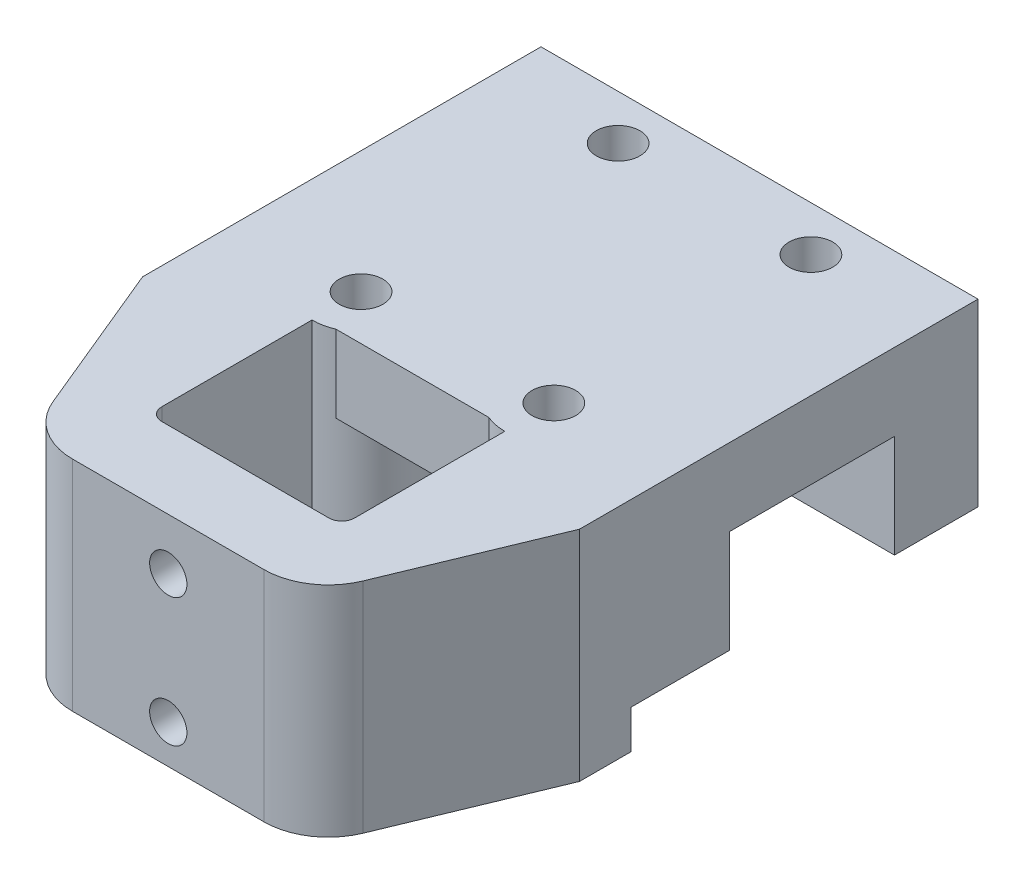
SolidWorks part; units mm, degrees
ref_plane "Front" through (0, 0, 0) normal (0, 0, 1) x (1, 0, 0)
ref_plane "Top" through (0, 0, 0) normal (0, 1, 0) x (1, 0, 0)
ref_plane "Right" through (0, 0, 0) normal (1, 0, 0) x (0, 0, -1)
sketch "Sketch1" plane through (0, 0, 0) normal (0, 1, 0) x (1, 0, 0)
  line B0 (17, 0) -> (0, 0) construction
  line B1 (17, -12) -> (11, -12)
  line B2 (17, -12) -> (17, 12)
  line B3 (17, 12) -> (11, 12)
  line B4 (-17, -12) -> (-17, 12)
  line B5 (-11, 12) -> (-11, 13.5)
  line B6 (11, -13.5) -> (-11, -13.5)
  line B7 (11, -13.5) -> (11, -12)
  line B8 (11, 13.5) -> (-11, 13.5)
  line B9 (-11, -13.5) -> (-11, -12)
  line B10 (-11, 12) -> (-17, 12)
  line B11 (-11, -12) -> (-17, -12)
  line B12 (0, 13.5) -> (0, 0) construction
  line B13 (7.5, -10) -> (-7.5, -10) construction
  line B14 (7.5, -10) -> (7.5, 10) construction
  line B15 (7.5, 10) -> (-7.5, 10) construction
  line B16 (-7.5, -10) -> (-7.5, 10) construction
  line B17 (7.5, -10) -> (-7.5, 10) construction
  line B18 (7.5, 10) -> (-7.5, -10) construction
sketch_block_instance "TW-04-12-1"
sketch_block "TW-04-12" parameters "D1"=22, "D2"=34, "D3"=27, "D4"=24, "D5"=20, "D6"=15
sketch "Sketch2" plane through (0, 0, 0) normal (0, 1, 0) x (1, 0, 0)
  line L0 (7.5, -9.8166) -> (-7.5, -9.8166) construction
  line L1 (7.5, -10) -> (7.5, 10) construction
  line L2 (7.5, -5.8166) -> (186, -5.8166) construction
  line L4 (-186, -5.8166) -> (-7.5, -5.8166)
  line L5 (-3.7504, -11.2097) -> (-5.4525, -15.7909)
  line L6 (5.4525, -15.7909) -> (3.7504, -11.2097)
  line L7 (7.5, -5.8166) -> (186, -5.8166)
  line L8 (186, 5.8166) -> (-186, 5.8166)
  line L11 (0, -17.8166) -> (0, 0) construction
  line L13 (-186, 0) -> (186, 0) construction
  arc A0 (-186, 5.8166) -> (-186, -5.8166) centre (-186, 0) ccw
  arc A1 (-7.5, -5.8166) -> (-3.7504, -11.2097) centre (-7.5, -9.8166) cw
  arc A2 (-5.4525, -15.7909) -> (5.4525, -15.7909) centre (0, -17.8166) ccw
  arc A4 (3.7504, -11.2097) -> (7.5, -5.8166) centre (7.5, -9.8166) cw
  arc A5 (186, -5.8166) -> (186, 5.8166) centre (186, 0) ccw
  circle B0 centre (186, 0) radius 5.8166
  circle B1 centre (-186, 0) radius 5.8166
  circle B2 centre (0, -17.8166) radius 5.8166
  circle B3 centre (7.5, -9.8166) radius 4
  circle B4 centre (-7.5, -9.8166) radius 4
  dimension "D1" = 8
  dimension "D7" = 372
sketch_block_instance "MXL-Pulley1163mmpd-1"
sketch_block "MXL-Pulley1163mmpd" parameters "D1"=11.6332
sketch_block_instance "MXL-Pulley1163mmpd-2"
sketch_block_instance "MXL-Pulley1163mmpd-4"
sketch_block_instance "Belt Guide Curve-1"
sketch_block "Belt Guide Curve" parameters "D1"=4.7507
sketch_block_instance "Belt Guide Curve-2"
other "Belt1"
sketch "Sketch3" plane through (0, 0, 0) normal (0, 1, 0) x (1, 0, 0)
  line L0 (11, 13.5) -> (-11, 13.5) construction
  line L1 (17, 13.5) -> (-17, 13.5)
  line L2 (17, 13.5) -> (17, -32.5)
  line L3 (17, -32.5) -> (-17, -32.5)
  line L4 (-17, 13.5) -> (-17, -32.5)
  line L5 (17, -12) -> (17, 12) construction
  line L6 (-17, -12) -> (-17, 12) construction
  dimension "D1" = 46
extrude "Boss-Extrude1" add sketch "Sketch3" against normal blind 14
hole_wizard "M3 Clearance Hole1" positions "Sketch5" profile "Sketch4" hole size "M3" standard "Ansi Metric" end condition through all
sketch "Sketch5" plane through (0, 0, 0) normal (0, 1, 0) x (-1, 0, 0)
  point P0 (7.5, 10)
  point P1 (7.5, -10)
  point P4 (-7.5, -10)
  point P7 (-7.5, 10)
sketch "Sketch4" plane through (-7.5, 0, 10) normal (1, 0, 0) x (0, 0, 1)
  line L0 (0, 0) -> (0, 14)
  line L1 (0, 14) -> (1.7, 14)
  line L2 (1.7, 14) -> (1.7, 0)
  line L5 (1.7, 0) -> (0, 0)
  line L11 (0, -6.35) -> (0, 107.95) construction
  dimension "Thru Hole Dia." = 3.4
  dimension "Thru Hole Depth" = 14
sketch "Sketch6" plane through (0, 0, 0) normal (1, 0, 0) x (0, 0, -1)
  line L0 (-32.5, -14) -> (13.5, -14) construction
  line L1 (-5.8166, -14) -> (7, -14)
  line L2 (-5.8166, -14) -> (-5.8166, -6)
  line L3 (-5.8166, -6) -> (7, -6)
  line L4 (7, -14) -> (7, -6)
  line L5 (13.5, -14) -> (13.5, 0) construction
  point P8 (-5.8166, 0)
  dimension "D1" = 6.5
  dimension "D2" = 8
  dimension "D3" = 12.8166
extrude "Cut-Extrude1" cut sketch "Sketch6" against normal through all and the other way through all
sketch "Sketch7" plane through (0, -6, 0) normal (0, 1, 0) x (1, 0, 0)
  line L1 (-7.5, -26.5) -> (7.5, -26.5)
  line L3 (0, -17.8166) -> (0, 0) construction
  line L4 (0, -17.8166) -> (0, 0) construction
  line L5 (-17, -32.5) -> (17, -32.5) construction
  line L6 (-17, -5.8166) -> (17, -5.8166) construction
  line L7 (-7.5, -5.8166) -> (7.5, -5.8166)
  line L8 (-7.5, -13.8166) -> (-7.5, -26.5)
  line L9 (7.5, -13.8166) -> (7.5, -26.5)
  arc A0 (-7.5, -13.8166) -> (-7.5, -5.8166) centre (-7.5, -9.8166) ccw
  arc A1 (7.5, -5.8166) -> (7.5, -13.8166) centre (7.5, -9.8166) ccw
  circle A2 centre (7.5, -9.8166) radius 4 construction
  circle A3 centre (-7.5, -9.8166) radius 4 construction
  dimension "D2" = 15
  dimension "D1" = 6
extrude "Cut-Extrude2" cut sketch "Sketch7" against normal through all
sketch "Sketch12" plane through (0, -6, 0) normal (0, -1, 0) x (1, 0, 0)
  line L1 (11, 13.5) -> (-11, 13.5) construction
  line L3 (5.9403, 13.5) -> (-5.9403, 13.5)
  line L16 (7.5, 26.5) -> (-7.5, 26.5)
  line L17 (-7.5, 26.5) -> (-7.5, 13.8166)
  line L19 (-7.5, 5.8166) -> (-17, 5.8166)
  line L20 (-17, 5.8166) -> (-17, -7)
  line L21 (-17, -7) -> (17, -7)
  line L22 (17, -7) -> (17, 5.8166)
  line L23 (17, 5.8166) -> (7.5, 5.8166)
  line L25 (7.5, 13.8166) -> (7.5, 26.5)
  line L29 (7.5, 26.5) -> (-7.5, 26.5)
  line L30 (-7.5, 26.5) -> (-7.5, 13.8166)
  line L38 (7.5, 13.8166) -> (7.5, 26.5)
  arc A8 (-7.5, 5.8166) -> (-7.5, 13.8166) centre (-7.5, 9.8166) ccw
  arc A9 (7.5, 13.8166) -> (7.5, 5.8166) centre (7.5, 9.8166) ccw
  arc A14 (-5.9403, 13.5) -> (-7.5, 13.8166) centre (-7.5, 9.8166) ccw
  arc A15 (7.5, 13.8166) -> (5.9403, 13.5) centre (7.5, 9.8166) ccw
  dimension "D1" = 0
chamfer "Chamfer1" distance 15 angle 22.5 2 edges at (-17, -7, 32.5) (17, -7, 32.5)
extrude "Cut-Extrude3" cut sketch "Sketch12" against normal up to next
sketch "Sketch14" plane through (0, -14, 0) normal (0, -1, 0) x (1, 0, 0)
  line L0 (-5.9403, 13.5) -> (5.9403, 13.5) construction
  line L1 (-17, 13.5) -> (-7.5, 13.5)
  line L2 (7.5, 13.5) -> (17, 13.5)
  line L10 (10.7868, 32.5) -> (-10.7868, 32.5)
  line L11 (-10.7868, 32.5) -> (-17, 17.5)
  line L12 (-17, 17.5) -> (-17, 5.8166)
  line L13 (-17, 5.8166) -> (-7.5, 5.8166)
  line L14 (-7.5, 13.8166) -> (-7.5, 26.5)
  line L15 (-7.5, 26.5) -> (7.5, 26.5)
  line L16 (7.5, 26.5) -> (7.5, 13.8166)
  line L17 (7.5, 5.8166) -> (17, 5.8166)
  line L18 (17, 5.8166) -> (17, 17.5)
  line L19 (17, 17.5) -> (10.7868, 32.5)
  line L20 (10.7868, 32.5) -> (-10.7868, 32.5)
  line L21 (-10.7868, 32.5) -> (-17, 17.5)
  line L22 (-17, 17.5) -> (-17, 13.5)
  line L24 (-7.5, 13.5) -> (-7.5, 26.5)
  line L25 (-7.5, 26.5) -> (7.5, 26.5)
  line L26 (7.5, 26.5) -> (7.5, 13.5)
  line L28 (17, 13.5) -> (17, 17.5)
  line L29 (17, 17.5) -> (10.7868, 32.5)
  arc A2 (-7.5, 5.8166) -> (-7.5, 13.8166) centre (-7.5, 9.8166) ccw
  arc A3 (7.5, 13.8166) -> (7.5, 5.8166) centre (7.5, 9.8166) ccw
  dimension "D1" = 0
extrude "Boss-Extrude2" add sketch "Sketch14" along normal blind 3
sketch "Sketch9" plane through (0, 0, 32.5) normal (0, 0, 1) x (1, 0, 0)
  line L0 (0, -4) -> (0, -14) construction
  line L1 (-17, -14) -> (-7.5, -14) construction
  dimension "D1" = 10
fillet "Fillet1" radius 1 2 edges at (7.5, -8.5, 26.5) (-7.5, -8.5, 26.5)
hole_wizard "M2.5 Clearance Hole1" positions "Sketch11" profile "Sketch10" hole size "M2.5" standard "Ansi Metric"
sketch "Sketch11" plane through (0, 0, 32.5) normal (0, 0, 1) x (1, 0, 0)
  point P0 (0, -4)
  point P1 (0, -14)
sketch "Sketch10" plane through (0, -4, 32.5) normal (1, 0, 0) x (0, -1, 0)
  line L0 (0, 0) -> (0, 6)
  line L1 (0, 6) -> (1.45, 6)
  line L2 (1.45, 6) -> (1.45, 0)
  line L5 (1.45, 0) -> (0, 0)
  line L11 (0, -6.35) -> (0, 107.95) construction
  dimension "Thru Hole Dia." = 2.9
  dimension "Thru Hole Depth" = 6
fillet "Fillet2" radius 5 2 edges at (10.7868, -8.5, 32.5) (-10.7868, -8.5, 32.5)
